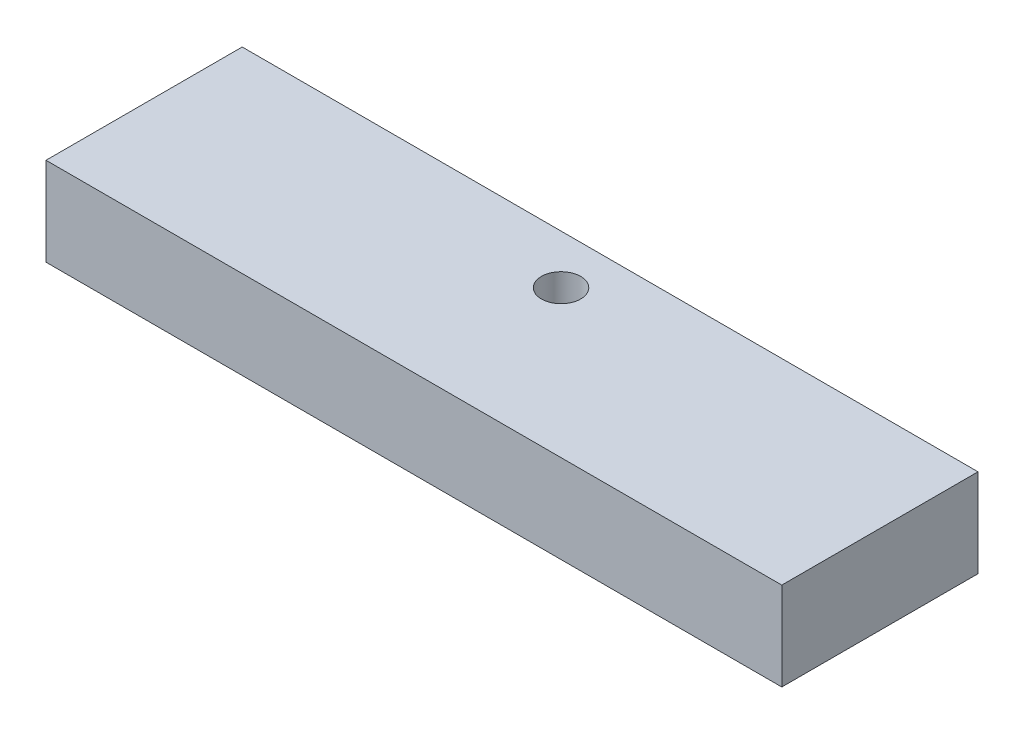
SolidWorks part; units mm, degrees
ref_plane "Front Plane" through (0, 0, 0) normal (0, 0, 1) x (1, 0, 0)
ref_plane "Top Plane" through (0, 0, 0) normal (0, 1, 0) x (1, 0, 0)
ref_plane "Right Plane" through (0, 0, 0) normal (1, 0, 0) x (0, 0, -1)
sketch "Sketch1" plane through (0, 0, 0) normal (0, 1, 0) x (1, 0, 0)
  line L0 (0, 20) -> (0, -20) construction
  line L1 (-75, -20) -> (75, -20)
  line L2 (-75, -20) -> (-75, 20)
  line L3 (-75, 20) -> (75, 20)
  line L4 (75, -20) -> (75, 20)
  line L5 (-75, -20) -> (75, 20) construction
  line L6 (-75, 20) -> (75, -20) construction
  circle A0 centre (0, 10) radius 4
  point P0 (0, 0)
  dimension "D3" = 8
  dimension "D1" = 150
  dimension "D2" = 40
  dimension "D4" = 10
extrude "Boss-Extrude1" add sketch "Sketch1" along normal blind 18
equation "\"Case_Width\" = 790mm"
equation "\"Case_Depth\" = 470mm"
equation "\"Tank_Width\" = 660mm"
equation "\"WoodSheet_Thickness\" = 18mm"
equation "\"D1@Boss-Extrude1\"=\"WoodSheet_Thickness\""
